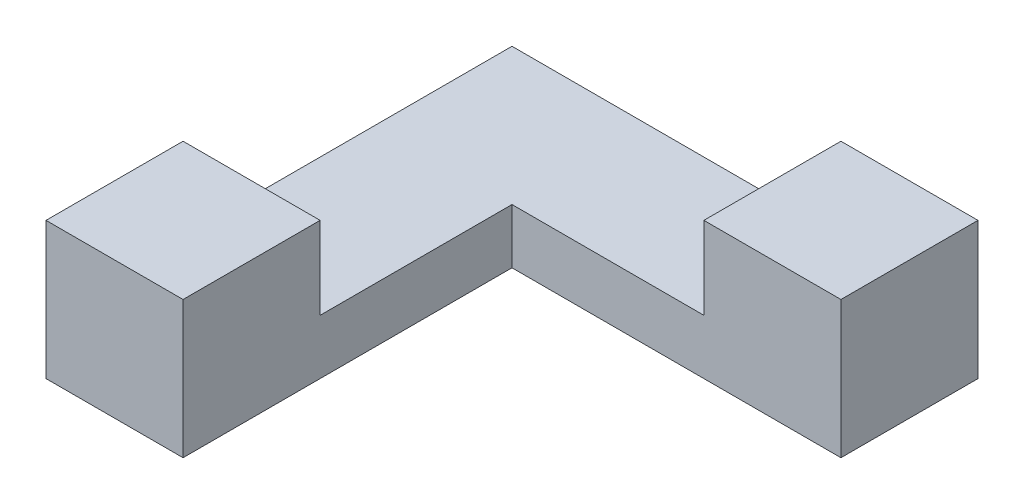
SolidWorks part; units mm, degrees
ref_plane "Front Plane" through (0, 0, 0) normal (0, 0, 1) x (1, 0, 0)
ref_plane "Top Plane" through (0, 0, 0) normal (0, 1, 0) x (1, 0, 0)
ref_plane "Right Plane" through (0, 0, 0) normal (1, 0, 0) x (0, 0, -1)
sketch "Sketch1" plane through (0, 0, 0) normal (0, 1, 0) x (1, 0, 0)
  line L0 (0, 0) -> (0, 7)
  line L1 (0, 7) -> (7, 7)
  line L2 (7, 7) -> (7, 12)
  line L3 (7, 12) -> (-5, 12)
  line L4 (-5, 12) -> (-5, 0)
  line L5 (-5, 0) -> (0, 0)
  dimension "D1" = 7
  dimension "D2" = 7
  dimension "D3" = 5
  dimension "D4" = 5
extrude "Boss-Extrude1" add sketch "Sketch1" along normal blind 2
sketch "Sketch2" plane through (0, 0, 0) normal (0, -1, 0) x (1, 0, 0)
  line L0 (7, -12) -> (-5, -12) construction
  line L1 (0, 0) -> (-5, 0)
  line L2 (0, 0) -> (0, 5)
  line L3 (0, 5) -> (-5, 5)
  line L4 (-5, 0) -> (-5, 5)
  line L5 (7, -7) -> (12, -7)
  line L6 (7, -7) -> (7, -12)
  line L7 (7, -12) -> (12, -12)
  line L8 (12, -7) -> (12, -12)
  line L9 (-5, -12) -> (-5, 0) construction
  dimension "D1" = 5
  dimension "D2" = 5
extrude "Boss-Extrude2" add sketch "Sketch2" against normal blind 5
